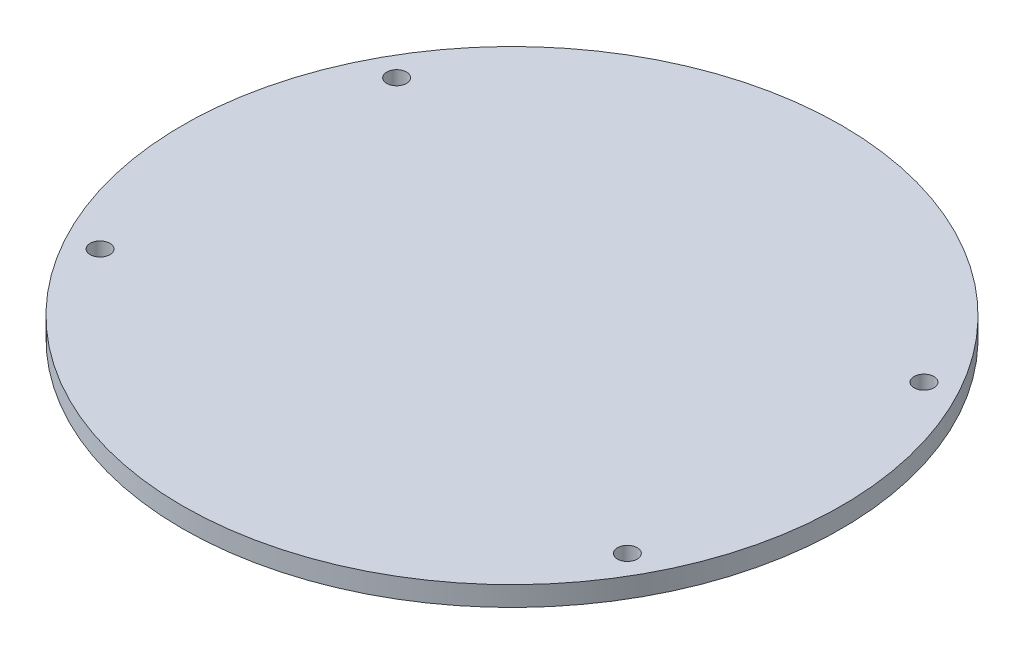
SolidWorks part; units mm, degrees
material "Cast Alloy Steel"
ref_plane "Front Plane" through (0, 0, 0) normal (0, 0, 1) x (1, 0, 0)
ref_plane "Top Plane" through (0, 0, 0) normal (0, 1, 0) x (1, 0, 0)
ref_plane "Right Plane" through (0, 0, 0) normal (1, 0, 0) x (0, 0, -1)
sketch "Sketch1" plane through (0, 0, 0) normal (0, 1, 0) x (1, 0, 0)
  line L1 (40, -22.5) -> (-40, -22.5) construction
  line L2 (40, -22.5) -> (40, 22.5) construction
  line L3 (40, 22.5) -> (-40, 22.5) construction
  line L4 (-40, -22.5) -> (-40, 22.5) construction
  line L5 (40, -22.5) -> (-40, 22.5) construction
  line L6 (40, 22.5) -> (-40, -22.5) construction
  circle A0 centre (0, 0) radius 50
  circle A1 centre (-40, 22.5) radius 1.5
  circle A2 centre (40, 22.5) radius 1.5
  circle A3 centre (40, -22.5) radius 1.5
  circle A4 centre (-40, -22.5) radius 1.5
  dimension "D1" = 100
  dimension "D4" = 3
  dimension "D2" = 80
  dimension "D3" = 45
extrude "Boss-Extrude1" add sketch "Sketch1" along normal blind 3
